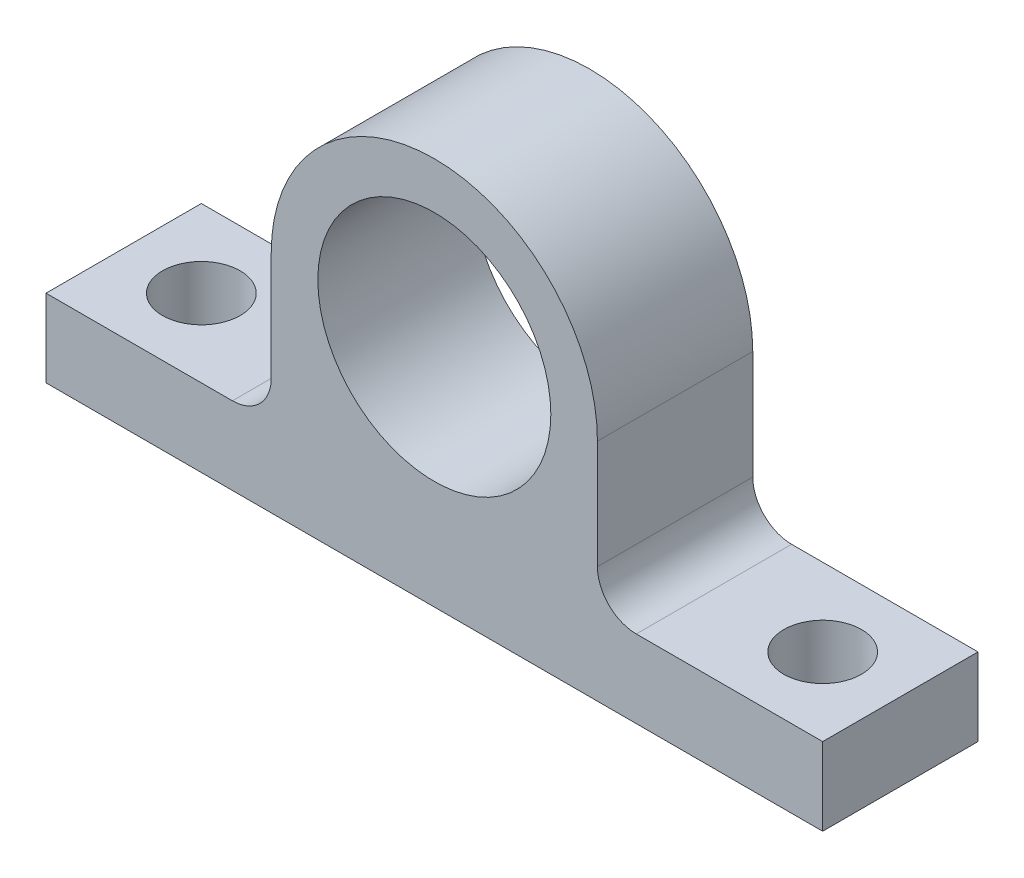
SolidWorks part; units mm, degrees
ref_plane "Front Plane" through (0, 0, 0) normal (0, 0, 1) x (1, 0, 0)
ref_plane "Top Plane" through (0, 0, 0) normal (0, 1, 0) x (1, 0, 0)
ref_plane "Right Plane" through (0, 0, 0) normal (1, 0, 0) x (0, 0, -1)
sketch "Sketch1" plane through (0, 0, 0) normal (0, 0, 1) x (1, 0, 0)
  line L0 (0, 0) -> (0, 14.5) construction
  line L1 (25, 0) -> (-25, 0)
  line L2 (-25, 0) -> (-25, 5)
  line L3 (-25, 5) -> (-13, 5)
  line L4 (-10.5, 14.5) -> (-10.5, 7.5)
  line L5 (10.5, 14.5) -> (10.5, 7.5)
  line L6 (25, 5) -> (13, 5)
  line L7 (25, 0) -> (25, 5)
  circle A0 centre (0, 14.5) radius 7.5
  arc A1 (10.5, 14.5) -> (-10.5, 14.5) centre (0, 14.5) ccw
  arc A2 (-10.5, 7.5) -> (-13, 5) centre (-13, 7.5) cw
  arc A3 (10.5, 7.5) -> (13, 5) centre (13, 7.5) ccw
  dimension "D1" = 2.5
extrude "Boss-Extrude1" add sketch "Sketch1" along normal blind 10
sketch "Sketch3" plane through (0, 5, 0) normal (0, 1, 0) x (1, 0, 0)
  line L2 (0, 0) -> (0, 1.3774) construction
  circle A0 centre (-20, -5) radius 2.5
  circle A1 centre (20, -5) radius 2.5
extrude "Cut-Extrude1" cut sketch "Sketch3" against normal blind 22
